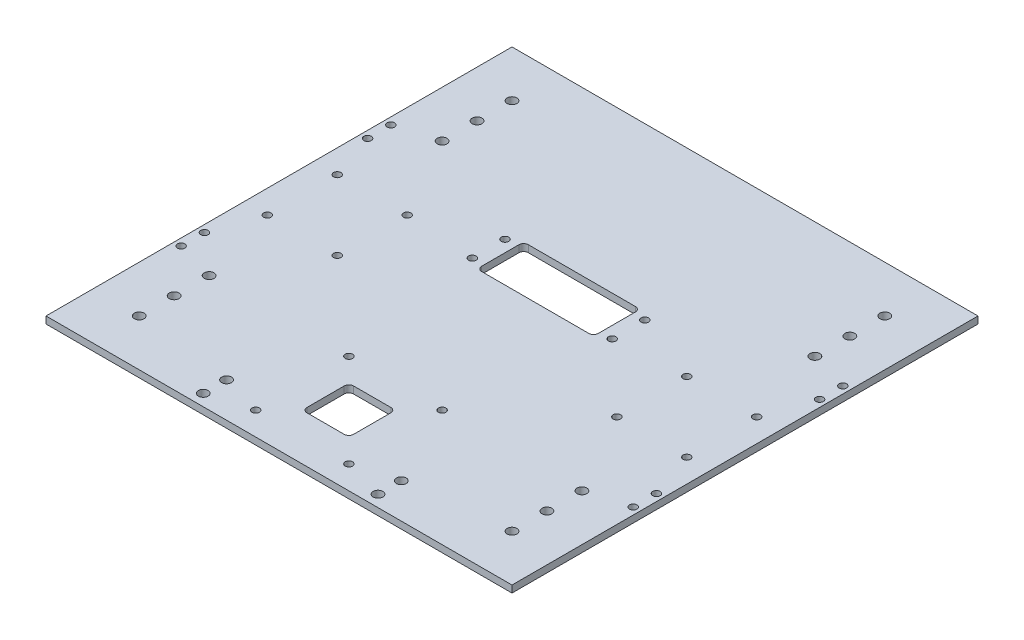
SolidWorks part; units mm, degrees
material "6061 合金"
ref_plane "前视基准面" through (0, 0, 0) normal (0, 0, 1) x (1, 0, 0)
ref_plane "上视基准面" through (0, 0, 0) normal (0, 1, 0) x (1, 0, 0)
ref_plane "右视基准面" through (0, 0, 0) normal (1, 0, 0) x (0, 0, -1)
sketch "草图1" plane through (0, 0, 0) normal (0, 1, 0) x (1, 0, 0)
  line L0 (-100, 0) -> (0, 0) construction
  line L1 (-100, -100) -> (100, -100)
  line L2 (-100, -100) -> (-100, 100)
  line L3 (-100, 100) -> (100, 100)
  line L4 (100, -100) -> (100, 100)
  line L5 (-100, -100) -> (100, 100) construction
  line L6 (-100, 100) -> (100, -100) construction
  line L7 (0, 100) -> (0, 0) construction
  line L8 (0, -100) -> (0, 0) construction
  line L13 (-23, 10) -> (23, 10)
  line L16 (-25, 12) -> (-25, 28)
  line L19 (-23, 30) -> (23, 30)
  line L22 (25, 12) -> (25, 28)
  line L23 (-25, 10) -> (25, 30) construction
  line L26 (-25, 30) -> (25, 10) construction
  line L30 (-8, -80) -> (8, -80)
  line L31 (-10, -78) -> (-10, -62)
  line L32 (-8, -60) -> (8, -60)
  line L33 (10, -78) -> (10, -62)
  line L34 (-10, -80) -> (10, -60) construction
  line L35 (-10, -60) -> (10, -80) construction
  circle A0 centre (-97, 35) radius 1.6
  circle A1 centre (-97, 45) radius 1.6
  circle A2 centre (-97, -45) radius 1.6
  circle A3 centre (-97, -35) radius 1.6
  circle A4 centre (97, -45) radius 1.6
  circle A5 centre (97, -35) radius 1.6
  circle A6 centre (97, 35) radius 1.6
  circle A7 centre (97, 45) radius 1.6
  circle A36 centre (-37.5, -95) radius 2.1
  circle A37 centre (-37.5, -85) radius 2.1
  circle A38 centre (37.5, -85) radius 2.1
  circle A39 centre (37.5, -95) radius 2.1
  circle A40 centre (-20, -50) radius 1.6
  circle A41 centre (20, -50) radius 1.6
  circle A42 centre (20, -90) radius 1.6
  circle A43 centre (-20, -90) radius 1.6
  circle A44 centre (-30, 27) radius 1.6
  circle A45 centre (-30, 13) radius 1.6
  circle A46 centre (30, 13) radius 1.6
  circle A47 centre (30, 27) radius 1.6
  arc A48 (23, 10) -> (25, 12) centre (23, 12) ccw
  arc A49 (23, 30) -> (25, 28) centre (23, 28) cw
  arc A50 (-23, 10) -> (-25, 12) centre (-23, 12) cw
  arc A51 (-25, 28) -> (-23, 30) centre (-23, 28) cw
  arc A52 (-8, -80) -> (-10, -78) centre (-8, -78) cw
  arc A53 (8, -80) -> (10, -78) centre (8, -78) ccw
  arc A54 (8, -60) -> (10, -62) centre (8, -62) cw
  arc A55 (-10, -62) -> (-8, -60) centre (-8, -62) cw
  circle A56 centre (-80, 50) radius 2.1
  circle A57 centre (-80, 65) radius 2.1
  circle A58 centre (-80, 80) radius 2.1
  circle A59 centre (80, 80) radius 2.1
  circle A60 centre (80, 65) radius 2.1
  circle A61 centre (80, 50) radius 2.1
  circle A62 centre (80, -80) radius 2.1
  circle A63 centre (80, -65) radius 2.1
  circle A64 centre (80, -50) radius 2.1
  circle A65 centre (-80, -80) radius 2.1
  circle A66 centre (-80, -65) radius 2.1
  circle A67 centre (-80, -50) radius 2.1
  circle A68 centre (-90, 15) radius 1.6
  circle A69 centre (-60, 15) radius 1.6
  circle A70 centre (-60, -15) radius 1.6
  circle A71 centre (-90, -15) radius 1.6
  circle A72 centre (90, -15) radius 1.6
  circle A73 centre (60, -15) radius 1.6
  circle A74 centre (60, 15) radius 1.6
  circle A75 centre (90, 15) radius 1.6
  point P0 (0, 0)
  point P27 (0, 20)
  point P59 (0, -70)
  dimension "D3" = 3.2
  dimension "D4" = 35
  dimension "D5" = 3
  dimension "D7" = 3.2
  dimension "D8" = 50
  dimension "D12" = 37.5
  dimension "D13" = 95
  dimension "D14" = 2
  dimension "D11" = 4.2
  dimension "D9" = 20
  dimension "D19" = 3.2
  dimension "D20" = 5
  dimension "D21" = 3
  dimension "D23" = 2
  dimension "D27" = 2
  dimension "D28" = 4.2
  dimension "D29" = 80
  dimension "D31" = 50
  dimension "D32" = 3.2
  dimension "D33" = 15
  dimension "D34" = 10
  dimension "D1" = 200
  dimension "D2" = 200
  dimension "D16" = 50
  dimension "D17" = 20
  dimension "D18" = 70
  dimension "D24" = 20
  dimension "D25" = 20
  dimension "D26" = 20
  dimension "D6" = 2
  dimension "D10" = 2
  dimension "D15" = 2
  dimension "D22" = 2
  dimension "D30" = 3
  dimension "D35" = 2
  dimension "D36" = 2
extrude "凸台-拉伸1" add sketch "草图1" along normal blind 3
